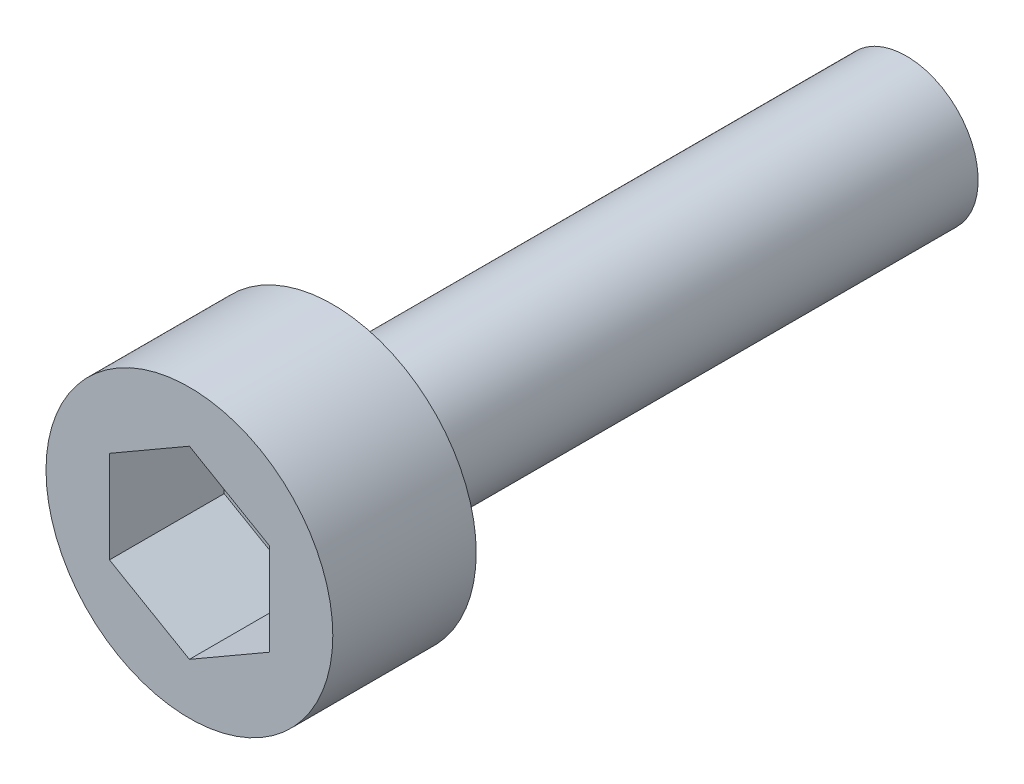
SolidWorks part; units mm, degrees
ref_plane "Front Plane" through (0, 0, 0) normal (0, 0, 1) x (1, 0, 0)
ref_plane "Top Plane" through (0, 0, 0) normal (0, 1, 0) x (1, 0, 0)
ref_plane "Right Plane" through (0, 0, 0) normal (1, 0, 0) x (0, 0, -1)
sketch "Sketch1" plane through (0, 0, 0) normal (0, 0, 1) x (1, 0, 0)
  circle A0 centre (367.0334, -490) radius 5
extrude "Boss-Extrude1" add sketch "Sketch1" along normal blind 5
sketch "Sketch2" plane through (0, 0, 0) normal (0, 0, -1) x (-1, 0, 0)
  circle A0 centre (-367.0334, -490) radius 2.5
extrude "Boss-Extrude2" add sketch "Sketch2" along normal blind 20
sketch "Sketch3" plane through (0, 0, 5) normal (0, 0, 1) x (1, 0, 0)
  line L1 (367.0334, -493.2182) -> (369.8205, -491.6091)
  line L2 (369.8205, -491.6091) -> (369.8205, -488.3909)
  line L3 (369.8205, -488.3909) -> (367.0334, -486.7818)
  line L4 (367.0334, -486.7818) -> (364.2464, -488.3909)
  line L5 (364.2464, -488.3909) -> (364.2464, -491.6091)
  line L6 (364.2464, -491.6091) -> (367.0334, -493.2182)
  circle A0 centre (367.0334, -490) radius 2.787 construction
extrude "Cut-Extrude1" cut sketch "Sketch3" against normal blind 4
